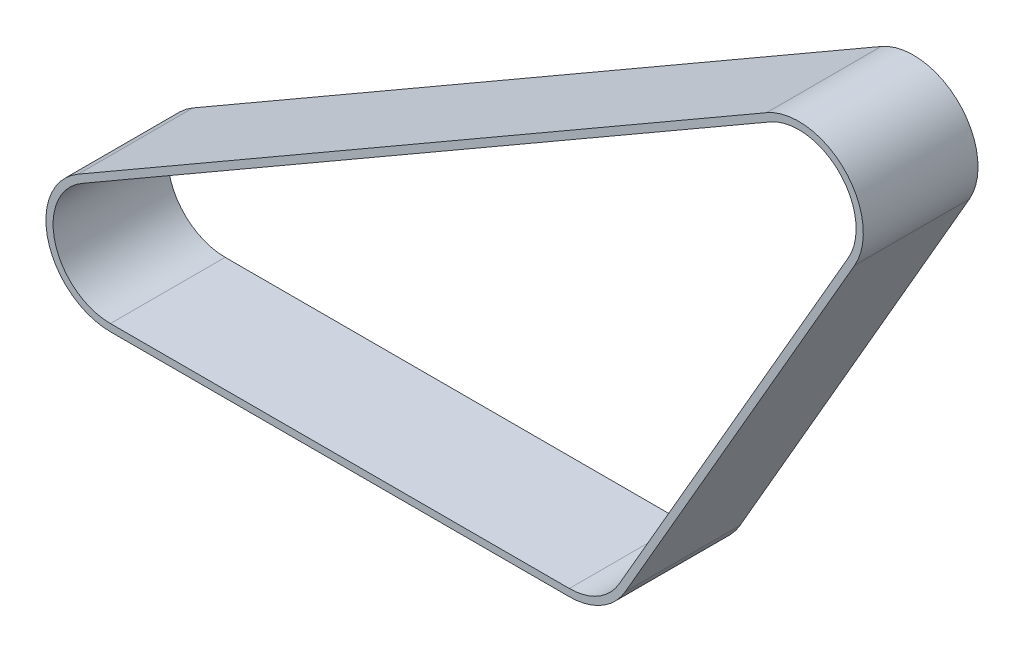
SolidWorks part; units mm, degrees
material "Silicon Rubber"
ref_plane "Front Plane" through (0, 0, 0) normal (0, 0, 1) x (1, 0, 0)
ref_plane "Top Plane" through (0, 0, 0) normal (0, 1, 0) x (1, 0, 0)
ref_plane "Right Plane" through (0, 0, 0) normal (1, 0, 0) x (0, 0, -1)
sketch "Sketch1" plane through (0, 0, 0) normal (0, 0, 1) x (1, 0, 0)
  line L0 (-101.6, 0) -> (0, 0) construction
  line L1 (0, 0) -> (50.8, 87.9882) construction
  line L2 (-101.6, -12.7) -> (0, -12.7)
  line L3 (-107.95, 10.9985) -> (44.45, 98.9867)
  line L4 (61.7985, 81.6382) -> (10.9985, -6.35)
  line L5 (43.6562, 100.3615) -> (-108.7438, 12.3733)
  line L6 (-101.6, -14.2875) -> (0, -14.2875)
  line L7 (12.3733, -7.1437) -> (63.1733, 80.8444)
  arc A0 (0, -12.7) -> (10.9985, -6.35) centre (0, 0) ccw
  arc A1 (61.7985, 81.6382) -> (44.45, 98.9867) centre (50.8, 87.9882) ccw
  arc A2 (-107.95, 10.9985) -> (-101.6, -12.7) centre (-101.6, 0) ccw
  arc A3 (-108.7438, 12.3733) -> (-101.6, -14.2875) centre (-101.6, 0) ccw
  arc A4 (0, -14.2875) -> (12.3733, -7.1437) centre (0, 0) ccw
  arc A5 (63.1733, 80.8444) -> (43.6562, 100.3615) centre (50.8, 87.9882) ccw
  point P1 (13.4619, -4.7864)
  dimension "D1" = 25.4
  dimension "D2" = 120
  dimension "D3" = 152.4
  dimension "D4" = 1.5875
extrude "Boss-Extrude1" add sketch "Sketch1" along normal blind 25.4
